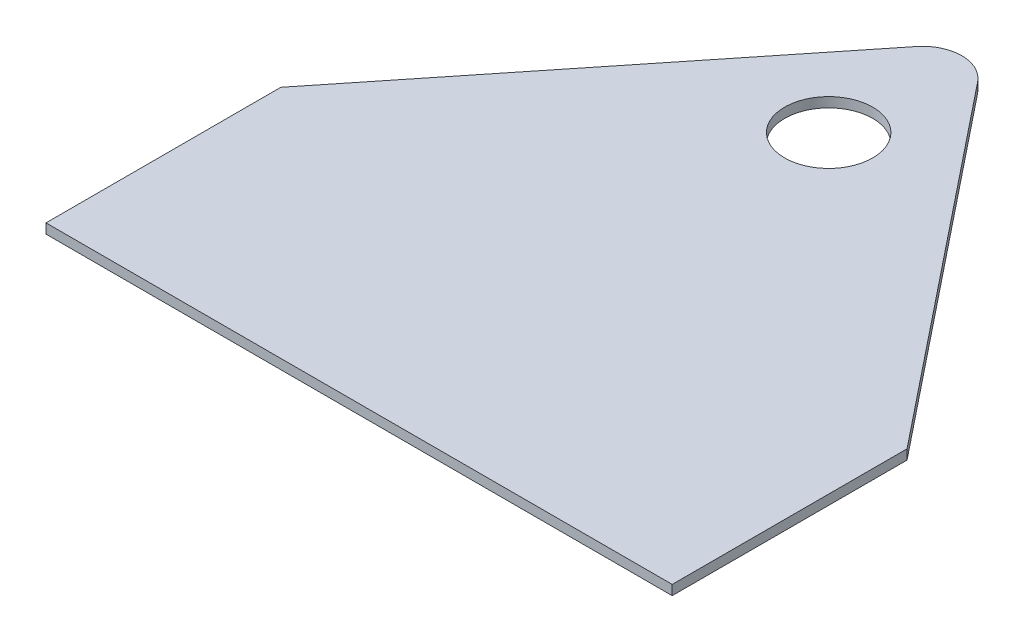
SolidWorks part; units mm, degrees
ref_plane "Front Plane" through (0, 0, 0) normal (0, 0, 1) x (1, 0, 0)
ref_plane "Top Plane" through (0, 0, 0) normal (0, 1, 0) x (1, 0, 0)
ref_plane "Right Plane" through (0, 0, 0) normal (1, 0, 0) x (0, 0, -1)
sketch "Sketch2" plane through (0, 0, 0) normal (0, 1, 0) x (1, 0, 0)
  line L0 (-101.6, 0) -> (101.6, 0)
  line L1 (-101.6, 0) -> (-101.6, 76.2)
  line L2 (-101.6, 76.2) -> (-9.917, 190.8037)
  line L3 (9.917, 190.8037) -> (101.6, 76.2)
  line L4 (101.6, 76.2) -> (101.6, 0)
  line L5 (0, 203.2) -> (0, 0) construction
  arc A0 (-9.917, 190.8037) -> (9.917, 190.8037) centre (0, 182.8701) cw
  point P4 (0, 0)
  dimension "D4" = 12.7
  dimension "D1" = 203.2
  dimension "D2" = 76.2
  dimension "D3" = 203.2
extrude "Boss-Extrude1" add sketch "Sketch2" along normal mid plane 3.175
sketch "Sketch3" plane through (0, 1.5875, 0) normal (0, 1, 0) x (1, 0, 0)
  line L0 (-9.917, 190.8037) -> (-101.6, 76.2) construction
  line L1 (101.6, 76.2) -> (9.917, 190.8037) construction
  circle A0 centre (0, 152.3752) radius 14.2875
  dimension "D1" = 28.575
  dimension "D2" = 31.75
  dimension "D3" = 31.75
extrude "Cut-Extrude1" cut sketch "Sketch3" against normal up to next
